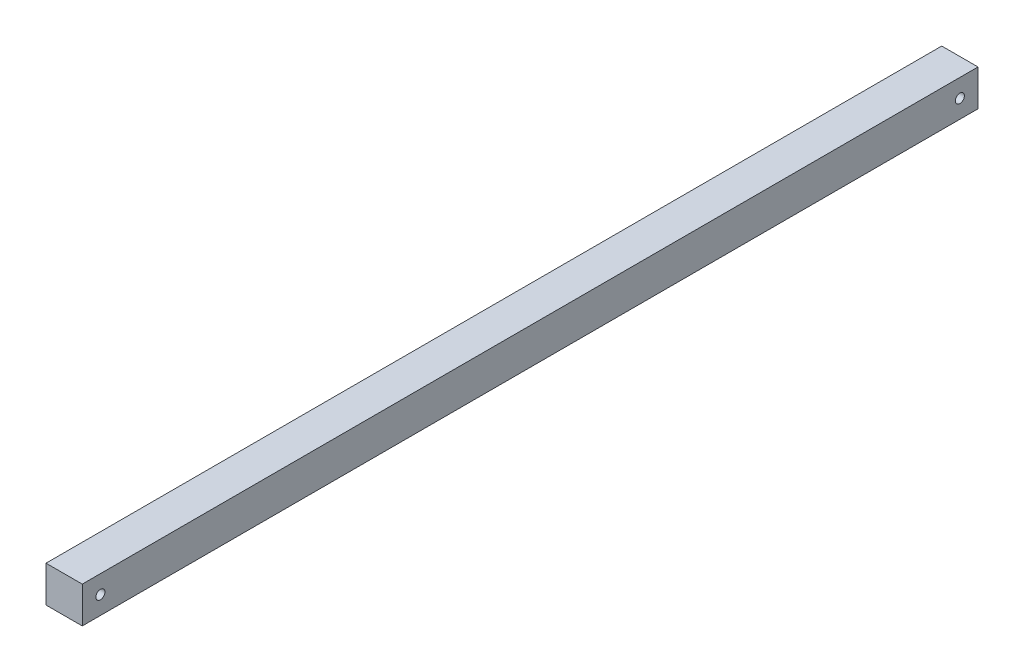
SolidWorks part; units mm, degrees
ref_plane "Plan de face" through (0, 0, 0) normal (0, 0, 1) x (1, 0, 0)
ref_plane "Plan de dessus" through (0, 0, 0) normal (0, 1, 0) x (1, 0, 0)
ref_plane "Plan de droite" through (0, 0, 0) normal (1, 0, 0) x (0, 0, -1)
sketch "Esquisse1" plane through (0, 0, 0) normal (0, 0, 1) x (1, 0, 0)
  line L0 (-5, 5) -> (5, -5) construction
  line L1 (-5, 5) -> (5, 5)
  line L2 (-5, 5) -> (-5, -5)
  line L3 (-5, -5) -> (5, -5)
  line L4 (5, 5) -> (5, -5)
  dimension "D1" = 10
extrude "Boss.-Extru.1" add sketch "Esquisse1" along normal up to surface (247 mm away)
hole_wizard "Trou taraudé M3x0.51" positions "Esquisse2" profile "Esquisse3" tap size "M3x0.5" standard "Ansi Metric" end condition through all
sketch "Esquisse2" plane through (-5, 0, 0) normal (-1, 0, 0) x (0, 0, 1)
  line L0 (0, 5) -> (0, -5) construction
  line L1 (247, -5) -> (247, 5) construction
  point P0 (242, 0)
  point P2 (5, 0)
  dimension "D1" = 5
  dimension "D2" = 5
sketch "Esquisse3" plane through (-5, 0, 242) normal (0, 1, 0) x (0, 0, 1)
  line L0 (0, 0) -> (0, 10)
  line L1 (0, 10) -> (1.25, 10)
  line L2 (1.25, 10) -> (1.25, 0)
  line L5 (1.25, 0) -> (0, 0)
  line L11 (0, -6.35) -> (0, 107.95) construction
  dimension "Diamètre du trou pour taraudage jusqu'au prochain" = 2.5
  dimension "Profondeur du trou pour taraudage jusqu'au prochain" = 10
cosmetic thread "Filetage de perçage1" parameters "D2"=3
cosmetic thread "Filetage de perçage2" parameters "D2"=3
